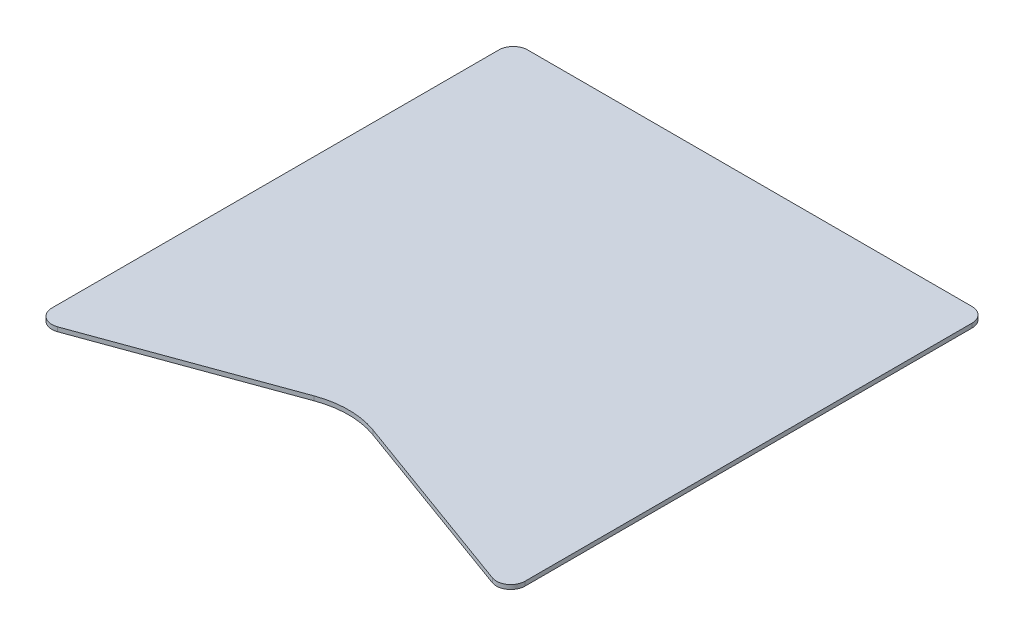
SolidWorks part; units mm, degrees
material "AISI 316 Stainless Steel Sheet (SS)"
ref_plane "Front Plane" through (0, 0, 0) normal (0, 0, 1) x (1, 0, 0)
ref_plane "Top Plane" through (0, 0, 0) normal (0, 1, 0) x (1, 0, 0)
ref_plane "Right Plane" through (0, 0, 0) normal (1, 0, 0) x (0, 0, -1)
sketch "Sketch3" plane through (0, 0, 0) normal (0, 1, 0) x (1, 0, 0)
  line L0 (165, 0) -> (998.6493, -303.4235)
  line L1 (0, 0) -> (330, 0)
  line L2 (0, 0) -> (0, 330)
  line L3 (0, 330) -> (330, 330)
  line L4 (330, 0) -> (330, 330)
  line L5 (0, 0) -> (330, 0)
  line L6 (0, 0) -> (0, -60.0551)
  line L7 (0, -60.0551) -> (330, -60.0551)
  line L8 (330, 0) -> (330, -60.0551)
  line L9 (165, 0) -> (-668.6493, -303.4235)
  line L10 (-668.6493, -319.3862) -> (165, -15.9627)
  line L11 (165, -15.9627) -> (998.6493, -319.3862)
  line L12 (-523.6468, -250.6469) -> (0, 0)
  line L13 (-668.6493, -303.4235) -> (0, 16.6298)
  line L14 (15, 0) -> (15, 315)
  line L15 (15, 315) -> (315, 315)
  line L16 (315, 0) -> (315, 315)
  line L17 (0, -25.0551) -> (330, -25.0551)
  line L18 (15, -10.0551) -> (315, -10.0551)
  line L19 (315, -10.0551) -> (315, 0)
  line L20 (15, 0) -> (15, -10.0551)
  line L21 (165, 330) -> (165, 0) construction
  line L22 (998.6493, -303.4235) -> (330, 16.6298)
  line L23 (853.6468, -250.6469) -> (330, 0)
  line L24 (15, 15) -> (315, 15)
  line L25 (-25, 32.3797) -> (15, 32.3797)
  line L26 (-25, 32.3797) -> (-7.7302, -3.7001)
  line L27 (-50, -51.6492) -> (-67.2698, -15.5693)
  line L28 (-50, -51.6492) -> (-36.3192, -89.2369)
  line L29 (165, -79.8133) -> (139.3485, -9.3364)
  line L30 (165, -79.8133) -> (190.6515, -9.3364)
  line L31 (0, 40) -> (15, 40) construction
  line L32 (-23.9741, 5.1545) -> (-17.4979, -8.3755) construction
  line L33 (127.6952, -13.5778) -> (132.8255, -27.6732) construction
  circle A0 centre (-50, -51.6492) radius 40
  circle A1 centre (-50, -51.6492) radius 25
  circle A2 centre (165, -79.8133) radius 75
  circle A3 centre (165, -79.8133) radius 60
  circle A4 centre (380, -51.6492) radius 25
  circle A5 centre (380, -51.6492) radius 40
  circle A6 centre (-25, 32.3797) radius 40
  circle A7 centre (-25, 32.3797) radius 25
  circle A8 centre (355, 32.3797) radius 25
  circle A9 centre (355, 32.3797) radius 40
  dimension "D5" = 150
  dimension "D10" = 80
  dimension "D13" = 80
  dimension "D1" = 330
  dimension "D2" = 330
  dimension "D3" = 15
  dimension "D4" = 15
  dimension "D7" = 15
  dimension "D8" = 35
  dimension "D9" = 70
  dimension "D11" = 50
  dimension "D12" = 15
  dimension "D14" = 290
  dimension "D15" = 48
  dimension "D16" = 180
  dimension "D6" = 15
extrude "Boss-Extrude1" add sketch "Sketch3" along normal blind 3 contours L14 L24 L16 L15 | L16 A9 L4 L3 L2 A6 L14 L15 | L25 A6 L2 | L2 A6 L25 | L26 A6 L2 L13 | L13 A6 L26 | A6 L13 A0 L12 | L12 A0 L27 | L27 A0 L12 | A1 L12 A0 L9 | L9 A0 L28 | L28 A0 L9 | A1 L9 A0 L12 | A0 L9 L6 L12 | A0 L10 L7 L9 | L17 L6 L9 | L20 L1 L6 L17 L9 L18 | A6 L2 L1 L14 | L24 L14 L5 L1 L16 | L5 L20 L18 L9 | A2 L17 L9 L7 L10 | L17 A2 L10 | A2 L18 L9 L17 | L18 A2 L17 L10 L29 | L11 L30 L18 L29 L10 | L29 A2 L18 | L30 A2 L29 L18 | A2 L0 L9 | L18 L19 L1 L0 | A3 L11 L10 | L17 A2 L18 L30 L11 | L11 A2 L17 | A2 L17 L0 L18 | L18 A2 L30 | L19 L18 L0 L17 L8 L5 | A2 L18 L0 | A2 L9 L18 | A6 L12 L2 | A2 L11 L7 L0 L17 | L17 L0 L8 | L11 A5 L0 L7 | L0 A5 L23 L8 | A5 L0 | A5 L23 A4 L0 | A4 | A5 L0 A4 L23 | A5 L23 | L22 A9 L23 A5 | A9 L22 L4 | L4 A9 L16 L5 | L23 A9 L4 | A9 L4 | L22 A8 L4 | A7 L13 L2
sketch "Sketch5" plane through (0, 0, 0) normal (0, 1, 0) x (1, 0, 0)
  line L0 (0, 58.3508) -> (0, -91.6492)
  line L1 (-90, 58.3508) -> (420, 58.3508) construction
  line L2 (-90, 58.3508) -> (-90, -91.6492) construction
  line L3 (-90, -91.6492) -> (420, -91.6492) construction
  line L4 (420, 58.3508) -> (420, -91.6492) construction
  line L5 (330, 58.3508) -> (420, 58.3508)
  line L6 (420, 58.3508) -> (420, -91.6492)
  line L8 (420, -91.6492) -> (-90, -91.6492)
  line L9 (330, -91.6492) -> (330, 58.3508)
  line L10 (-90, -91.6492) -> (-90, 58.3508)
  line L11 (0, 32.3797) -> (0, 330) construction
  line L14 (330, 32.3797) -> (330, 330) construction
  line L15 (-90, 58.3508) -> (0, 58.3508)
  arc A1 (366.3192, -89.2369) -> (397.2698, -15.5693) centre (380, -51.6492) ccw construction
  arc A2 (-67.2698, -15.5693) -> (-36.3192, -89.2369) centre (-50, -51.6492) ccw construction
  dimension "D1" = 150
extrude "Cut-Extrude3" cut sketch "Sketch5" along normal through all
sketch "Sketch6" plane through (0, 3, 0) normal (0, 1, 0) x (1, 0, 0)
  line L0 (330, -76.0178) -> (330, 330) construction
  line L1 (0, 330) -> (330, 330)
  line L2 (0, 330) -> (0, 260)
  line L3 (0, 260) -> (330, 260)
  line L4 (330, 330) -> (330, 260)
  dimension "D1" = 70
extrude "Cut-Extrude4" cut sketch "Sketch6" against normal through all
fillet "Fillet1" radius 10 4 edges at (330, 1.5, 76.0178) (0, 1.5, 76.0178) (330, 1.5, -260) (0, 1.5, -260)
